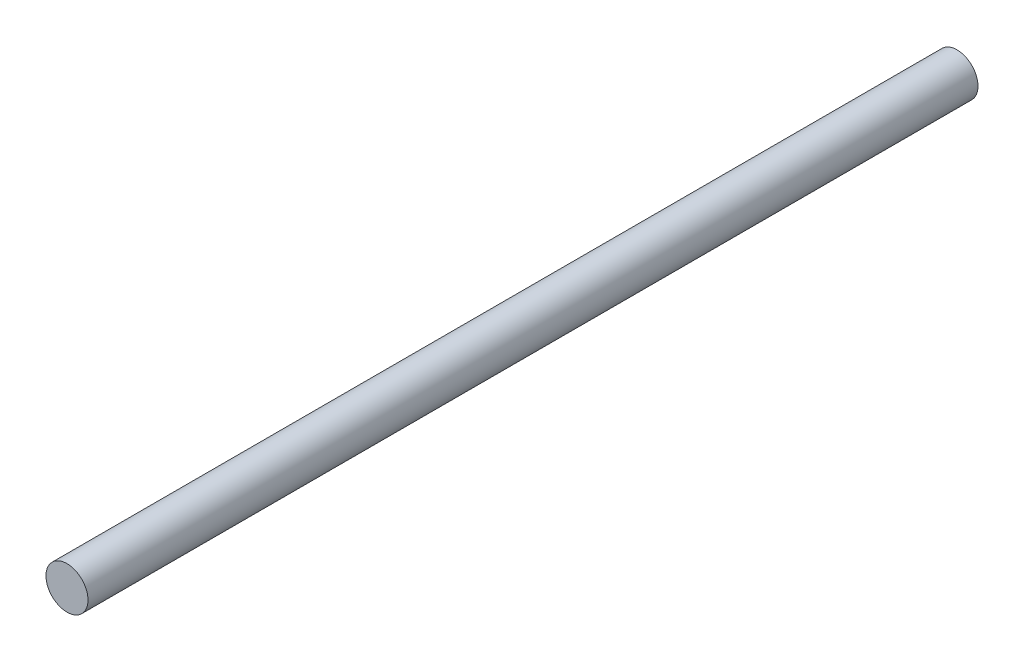
SolidWorks part; units mm, degrees
ref_plane "Front Plane" through (0, 0, 0) normal (0, 0, 1) x (1, 0, 0)
ref_plane "Top Plane" through (0, 0, 0) normal (0, 1, 0) x (1, 0, 0)
ref_plane "Right Plane" through (0, 0, 0) normal (1, 0, 0) x (0, 0, -1)
sketch "S01 - Thread major diameter" plane through (0, 0, 0) normal (0, 0, 1) x (1, 0, 0)
  circle A0 centre (0, 0) radius 3
  dimension "D1" = 6
extrude "01 - Thread major diameter" add sketch "S01 - Thread major diameter" along normal blind 127
